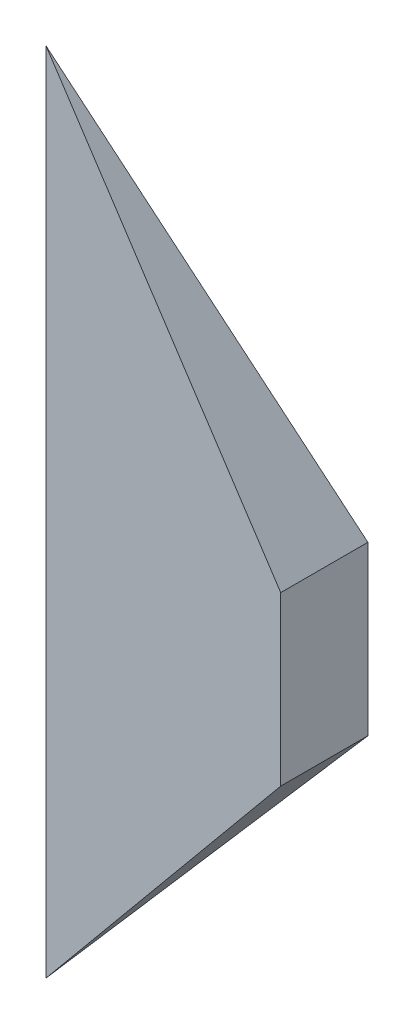
SolidWorks part; units mm, degrees
ref_plane "Plan de face" through (0, 0, 0) normal (0, 0, 1) x (1, 0, 0)
ref_plane "Plan de dessus" through (0, 0, 0) normal (0, 1, 0) x (1, 0, 0)
ref_plane "Plan de droite" through (0, 0, 0) normal (1, 0, 0) x (0, 0, -1)
sketch "Esquisse1" plane through (0, 0, 0) normal (0, 0, 1) x (1, 0, 0)
  line L0 (-7, -13.4585) -> (-7, 10.6244)
  line L1 (-7, 10.6244) -> (0, 0)
  line L3 (0, 0) -> (0, -5)
  line L4 (0, -5) -> (-7, -13.4585)
sketch "Esquisse2" plane through (0, 0, 0) normal (1, 0, 0) x (0, 0, -1)
  line L0 (0, 0) -> (0, -5)
  line L1 (0, -5) -> (2.6, -5)
  line L2 (2.6, -5) -> (2.6, 0)
  line L3 (2.6, 0) -> (0, 0)
  dimension "D1" = 2.6
loft "Lissage1" add profiles "Esquisse1", "Esquisse2"
